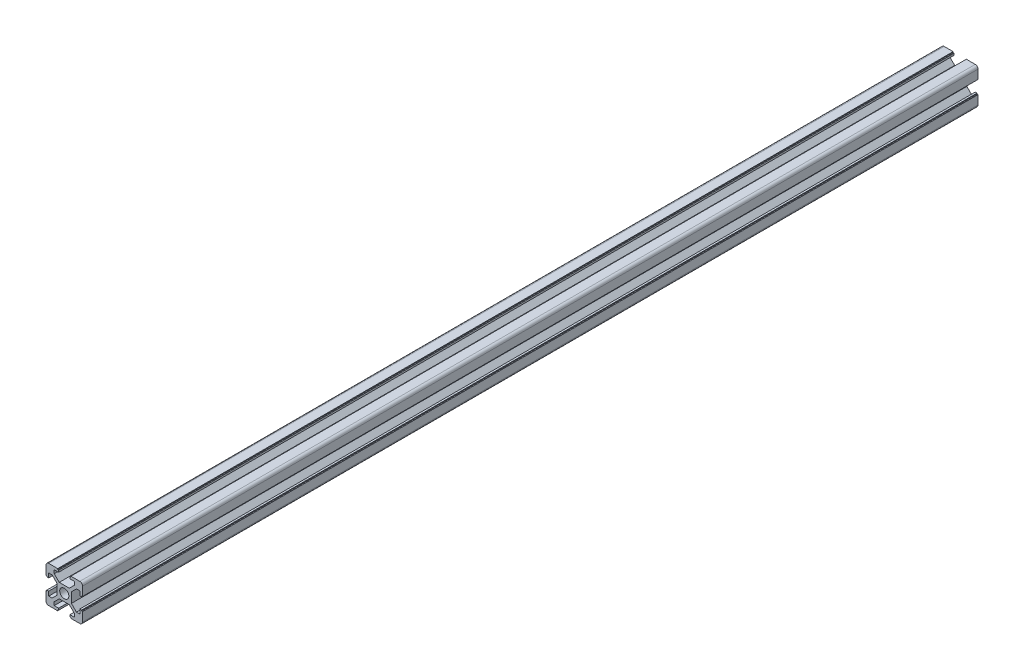
SolidWorks part; units mm, degrees
ref_plane "Plane1" through (0, 0, 0) normal (0, 0, 1) x (1, 0, 0)
ref_plane "Plane2" through (0, 0, 0) normal (0, 1, 0) x (1, 0, 0)
ref_plane "Plane3" through (0, 0, 0) normal (1, 0, 0) x (0, 0, -1)
sketch "Sketch1" plane through (0, 0, 0) normal (0, 0, 1) x (1, 0, 0)
  line L0 (-3.6, 10) -> (-3.6, 9.5)
  line L1 (-3.6, 9.5) -> (-3.1, 9.5)
  line L2 (-3.1, 9.5) -> (-3.1, 8.5)
  line L3 (-3.1, 8.5) -> (-5.5, 8.5)
  line L4 (-8.5, -10) -> (-3.6, -10)
  line L5 (-10, -8.5) -> (-10, -3.6)
  line L6 (8.5, 10) -> (3.6, 10)
  line L7 (10, 8.5) -> (10, 3.6)
  line L8 (0, 14.8756) -> (0, 0) construction
  line L9 (0, 0) -> (14.1675, 0) construction
  line L10 (-5.5, 8.5) -> (-5.5, 6.65)
  line L11 (-5.5, 6.65) -> (-2.75, 3.9)
  line L12 (-2.75, 3.9) -> (2.75, 3.9)
  line L13 (5.5, 6.65) -> (2.75, 3.9)
  line L14 (5.5, 8.5) -> (5.5, 6.65)
  line L15 (3.1, 8.5) -> (5.5, 8.5)
  line L16 (3.1, 9.5) -> (3.1, 8.5)
  line L17 (3.6, 9.5) -> (3.1, 9.5)
  line L18 (3.6, 10) -> (3.6, 9.5)
  line L19 (-3.6, 10) -> (-8.5, 10)
  line L20 (10, 3.6) -> (9.5, 3.6)
  line L21 (9.5, 3.6) -> (9.5, 3.1)
  line L22 (9.5, 3.1) -> (8.5, 3.1)
  line L23 (8.5, 3.1) -> (8.5, 5.5)
  line L24 (8.5, 5.5) -> (6.65, 5.5)
  line L25 (6.65, 5.5) -> (3.9, 2.75)
  line L26 (3.9, 2.75) -> (3.9, -2.75)
  line L27 (6.65, -5.5) -> (3.9, -2.75)
  line L28 (8.5, -5.5) -> (6.65, -5.5)
  line L29 (8.5, -3.1) -> (8.5, -5.5)
  line L30 (9.5, -3.1) -> (8.5, -3.1)
  line L31 (9.5, -3.6) -> (9.5, -3.1)
  line L32 (10, -3.6) -> (9.5, -3.6)
  line L33 (3.6, -10) -> (3.6, -9.5)
  line L34 (3.6, -9.5) -> (3.1, -9.5)
  line L35 (3.1, -9.5) -> (3.1, -8.5)
  line L36 (3.1, -8.5) -> (5.5, -8.5)
  line L37 (5.5, -8.5) -> (5.5, -6.65)
  line L38 (5.5, -6.65) -> (2.75, -3.9)
  line L39 (2.75, -3.9) -> (-2.75, -3.9)
  line L40 (-5.5, -6.65) -> (-2.75, -3.9)
  line L41 (-5.5, -8.5) -> (-5.5, -6.65)
  line L42 (-3.1, -8.5) -> (-5.5, -8.5)
  line L43 (-3.1, -9.5) -> (-3.1, -8.5)
  line L44 (-3.6, -9.5) -> (-3.1, -9.5)
  line L45 (-3.6, -10) -> (-3.6, -9.5)
  line L46 (-10, -3.6) -> (-9.5, -3.6)
  line L47 (-9.5, -3.6) -> (-9.5, -3.1)
  line L48 (-9.5, -3.1) -> (-8.5, -3.1)
  line L49 (-8.5, -3.1) -> (-8.5, -5.5)
  line L50 (-8.5, -5.5) -> (-6.65, -5.5)
  line L51 (-6.65, -5.5) -> (-3.9, -2.75)
  line L52 (-3.9, -2.75) -> (-3.9, 2.75)
  line L53 (-6.65, 5.5) -> (-3.9, 2.75)
  line L54 (-8.5, 5.5) -> (-6.65, 5.5)
  line L55 (-8.5, 3.1) -> (-8.5, 5.5)
  line L56 (-9.5, 3.1) -> (-8.5, 3.1)
  line L57 (-9.5, 3.6) -> (-9.5, 3.1)
  line L58 (-10, 3.6) -> (-9.5, 3.6)
  line L59 (3.6, -10) -> (8.5, -10)
  line L60 (-10, 3.6) -> (-10, 8.5)
  line L61 (10, -3.6) -> (10, -8.5)
  circle A0 centre (0, 0) radius 2.5
  arc A1 (-10, 8.5) -> (-8.5, 10) centre (-8.5, 8.5) cw
  arc A2 (10, 8.5) -> (8.5, 10) centre (8.5, 8.5) ccw
  arc A3 (-8.5, -10) -> (-10, -8.5) centre (-8.5, -8.5) cw
  arc A4 (8.5, -10) -> (10, -8.5) centre (8.5, -8.5) ccw
  point P0 (-10, 0)
  point P1 (10, 0)
  point P2 (0, 10)
  point P3 (0, -10)
  point P4 (0, 0)
  point P5 (-10, -10)
  point P6 (10, -10)
  point P7 (10, 10)
  point P8 (-10, 10)
  point P36 (-10, 10)
  point P39 (10, 10)
extrude "凸台-拉伸1" add sketch "Sketch1" along normal blind 490
sketch "草图1" plane through (0, 3.9, 0) normal (0, 1, 0) x (1, 0, 0)
  line L0 (2.75, -490) -> (-2.75, -490) construction
  circle A0 centre (0, -460) radius 1.5
  circle A2 centre (0, -441) radius 1.5
  dimension "D1" = 30
  dimension "D2" = 19
extrude "切除-拉伸2" cut sketch "草图1" against normal through all
